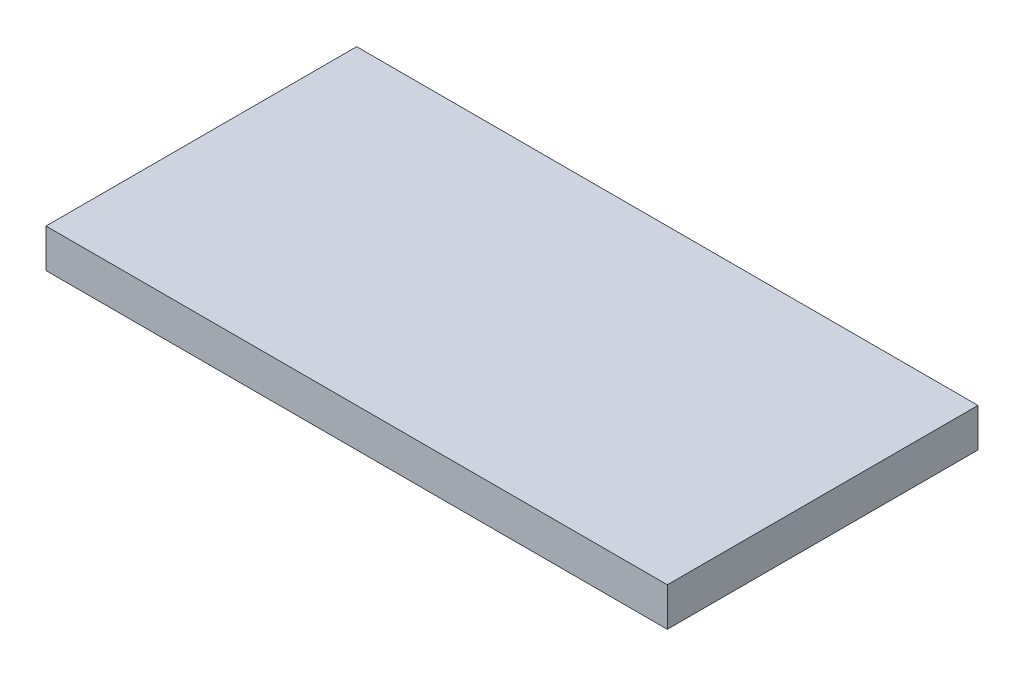
SolidWorks part; units mm, degrees
ref_plane "Alzado" through (0, 0, 0) normal (0, 0, 1) x (1, 0, 0)
ref_plane "Planta" through (0, 0, 0) normal (0, 1, 0) x (1, 0, 0)
ref_plane "Vista lateral" through (0, 0, 0) normal (1, 0, 0) x (0, 0, -1)
sketch "Croquis1" plane through (0, 0, 0) normal (0, 1, 0) x (1, 0, 0)
  line L1 (-50.8, 25.4) -> (50.8, 25.4)
  line L2 (-50.8, 25.4) -> (-50.8, -25.4)
  line L3 (-50.8, -25.4) -> (50.8, -25.4)
  line L4 (50.8, 25.4) -> (50.8, -25.4)
  line L5 (-50.8, 25.4) -> (50.8, -25.4) construction
  line L6 (-50.8, -25.4) -> (50.8, 25.4) construction
  point P0 (0, 0)
  dimension "D1" = 101.6
  dimension "D2" = 50.8
extrude "Saliente-Extruir1" add sketch "Croquis1" along normal blind 6.31
